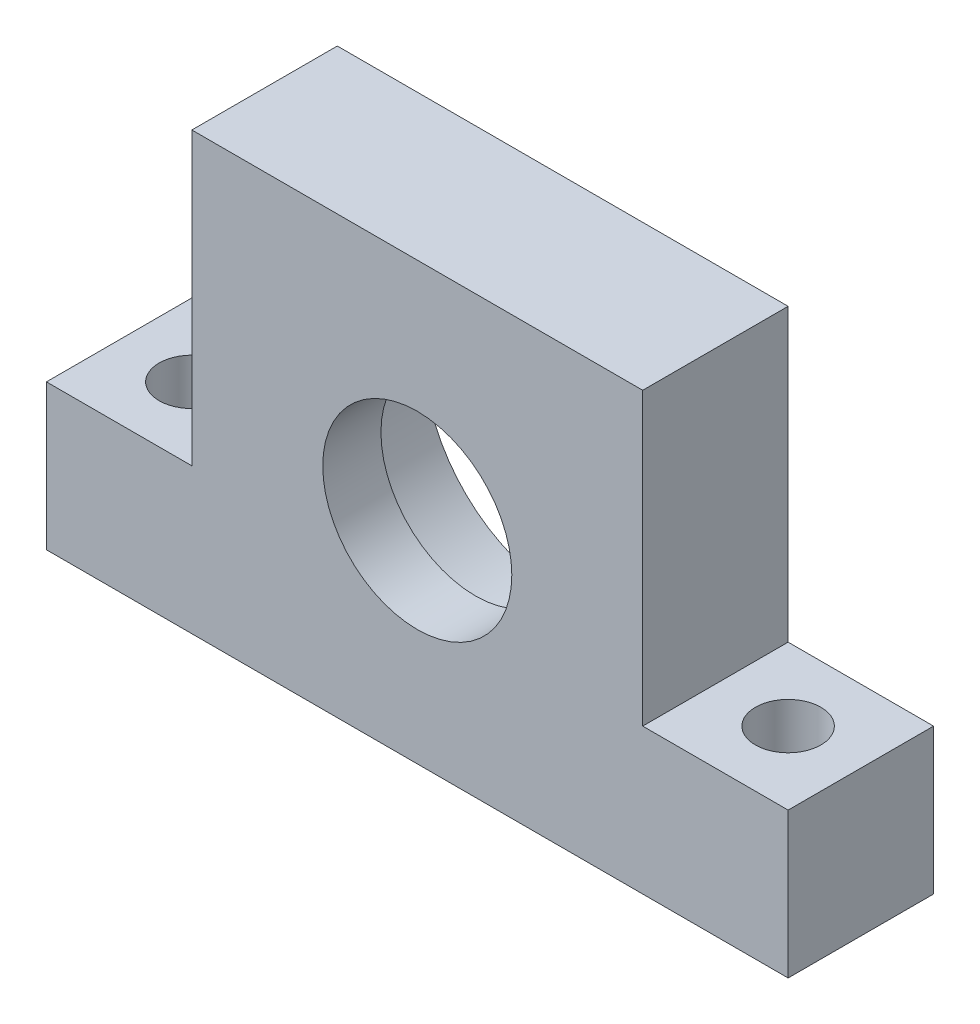
SolidWorks part; units mm, degrees
material "6061 Alloy"
ref_plane "Front Plane" through (0, 0, 0) normal (0, 0, 1) x (1, 0, 0)
ref_plane "Top Plane" through (0, 0, 0) normal (0, 1, 0) x (1, 0, 0)
ref_plane "Right Plane" through (0, 0, 0) normal (1, 0, 0) x (0, 0, -1)
sketch "Sketch1" plane through (0, 0, 0) normal (0, 0, 1) x (1, 0, 0)
  line L0 (-42.9536, -13.1966) -> (8.0464, -13.1966)
  line L1 (8.0464, -13.1966) -> (8.0464, -3.1966)
  line L2 (8.0464, -3.1966) -> (-1.9536, -3.1966)
  line L3 (-1.9536, -3.1966) -> (-1.9536, 16.8034)
  line L4 (-1.9536, 16.8034) -> (-32.9536, 16.8034)
  line L8 (-32.9536, 16.8034) -> (-32.9536, -3.1966)
  line L9 (-32.9536, -3.1966) -> (-42.9536, -3.1966)
  line L10 (-42.9536, -3.1966) -> (-42.9536, -13.1966)
extrude "Boss-Extrude1" add sketch "Sketch1" along normal blind 10
sketch "Sketch2" plane through (0, 0, 0) normal (0, 0, -1) x (-1, 0, 0)
  line L0 (17.4536, -13.1966) -> (17.4536, 1.3034) construction
  line L1 (42.9536, -13.1966) -> (-8.0464, -13.1966) construction
sketch "Sketch3" plane through (0, -3.1966, 0) normal (0, 1, 0) x (1, 0, 0)
  line L0 (3.0464, 0) -> (3.0464, -5) construction
  line L1 (8.0464, 0) -> (-1.9536, 0) construction
sketch "Sketch4" plane through (0, -3.1966, 0) normal (0, 1, 0) x (1, 0, 0)
  line L0 (-37.9536, 0) -> (-37.9536, -5) construction
  line L1 (-32.9536, 0) -> (-42.9536, 0) construction
sketch "Sketch5" plane through (0, 0, 0) normal (0, 0, -1) x (-1, 0, 0)
  circle A0 centre (17.4536, 1.3034) radius 6.5
extrude "Cut-Extrude1" cut sketch "Sketch5" against normal blind 10
sketch "Sketch7" plane through (0, 0, 0) normal (0, 0, -1) x (-1, 0, 0)
  circle A0 centre (17.4536, 1.3034) radius 9.5
extrude "Cut-Extrude2" cut sketch "Sketch7" against normal blind 6
sketch "Sketch8" plane through (0, -3.1966, 0) normal (0, 1, 0) x (1, 0, 0)
  circle A0 centre (3.0464, -5) radius 2.25
  circle A1 centre (-37.9536, -5) radius 2.25
extrude "Cut-Extrude3" cut sketch "Sketch8" against normal blind 15
